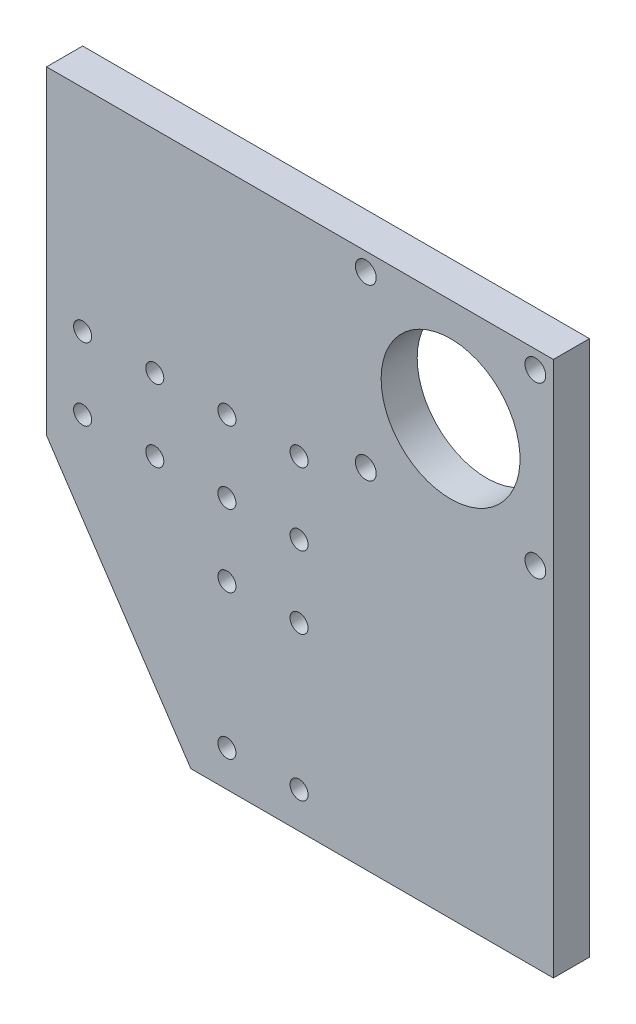
SolidWorks part; units mm, degrees
ref_plane "Front Plane" through (0, 0, 0) normal (0, 0, 1) x (1, 0, 0)
ref_plane "Top Plane" through (0, 0, 0) normal (0, 1, 0) x (1, 0, 0)
ref_plane "Right Plane" through (0, 0, 0) normal (1, 0, 0) x (0, 0, -1)
sketch "Sketch1" plane through (0, 0, 0) normal (0, 0, 1) x (1, 0, 0)
  line L0 (0, 0) -> (100.5, 0)
  line L1 (0, 0) -> (-40, 60)
  line L2 (-40, 60) -> (-40, 148.4989)
  line L3 (-40, 148.4989) -> (100.5, 148.4989)
  line L4 (100.5, 148.4989) -> (100.5, 0)
  point P3 (0, 0)
  point P8 (0, 0)
  point P9 (82.4679, 40)
  point P10 (84.0884, 40)
  point P11 (84.8987, 40)
  point P12 (84.8987, 0)
  point P13 (40, 0)
  point P14 (83.4195, 0)
  dimension "D1" = 100.5
  dimension "D2" = 60
  dimension "D3" = 40
  dimension "D4" = 148.4989
extrude "Boss-Extrude1" add sketch "Sketch1" along normal blind 10
sketch "Sketch3" plane through (0, 0, 0) normal (0, 0, -1) x (-1, 0, 0)
  line L0 (-100.5, 148.4989) -> (40, 148.4989) construction
  line L1 (-100.5, 0) -> (-100.5, 148.4989) construction
  line L2 (40, 148.4989) -> (40, 60) construction
  line L3 (0, 0) -> (-100.5, 0) construction
  circle A0 centre (-72, 119.9989) radius 19.25
  circle A1 centre (-30, 50) radius 2.5
  circle A2 centre (-10, 50) radius 2.5
  circle A3 centre (-30, 10) radius 2.5
  circle A4 centre (-10, 10) radius 2.5
  circle A5 centre (30, 70) radius 2.5
  circle A6 centre (30, 90) radius 2.5
  circle A7 centre (10, 90) radius 2.5
  circle A8 centre (10, 70) radius 2.5
  circle A9 centre (-10, 70) radius 2.5
  circle A10 centre (-10, 90) radius 2.5
  circle A11 centre (-30, 90) radius 2.5
  circle A12 centre (-30, 70) radius 2.5
  circle A13 centre (-95.5, 143.4989) radius 2.885
  circle A14 centre (-48.5, 143.4989) radius 2.885
  circle A15 centre (-48.5, 96.4989) radius 2.885
  circle A16 centre (-95.5, 96.4989) radius 2.885
  point P42 (0, 0)
  point P43 (0, 0)
  point P44 (0, 0)
  point P45 (0, 0)
  dimension "D1" = 38.5
  dimension "D5" = 20
  dimension "D8" = 5
  dimension "D16" = 47
  dimension "D2" = 28.5
  dimension "D3" = 28.5
  dimension "D4" = 20
  dimension "D6" = 10
  dimension "D7" = 10
  dimension "D9" = 70.5
  dimension "D10" = 40
  dimension "D11" = 20
  dimension "D12" = 70
  dimension "D13" = 20
  dimension "D14" = 20
  dimension "D15" = 20
  dimension "D17" = 47
  dimension "D18" = 5
  dimension "D19" = 5
extrude "Cut-Extrude1" cut sketch "Sketch3" against normal up to next
